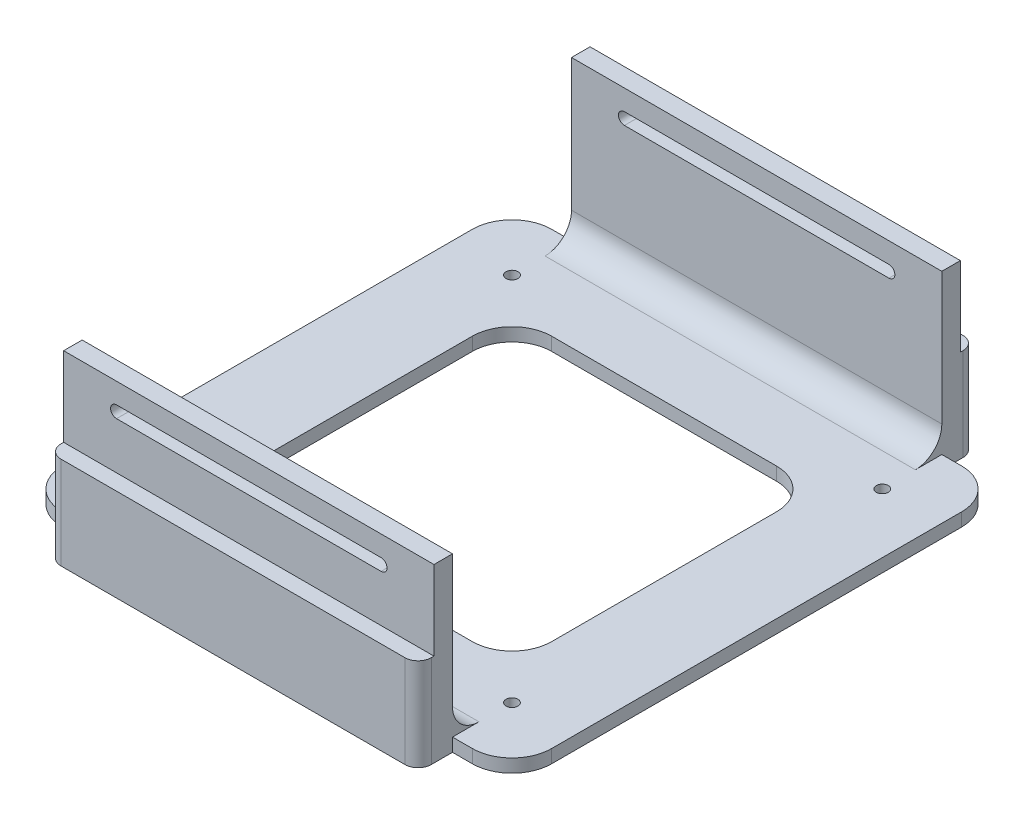
SolidWorks part; units mm, degrees
ref_plane "Front Plane" through (0, 0, 0) normal (0, 0, 1) x (1, 0, 0)
ref_plane "Top Plane" through (0, 0, 0) normal (0, 1, 0) x (1, 0, 0)
ref_plane "Right Plane" through (0, 0, 0) normal (1, 0, 0) x (0, 0, -1)
sketch "Sketch1" plane through (0, 0, 0) normal (0, 1, 0) x (1, 0, 0)
  line L0 (-60.9238, 116.5412) -> (-60.9238, 129.5412)
  line L1 (-83.4238, 116.5412) -> (101.5762, 116.5412)
  line L2 (-83.4238, 116.5412) -> (-83.4238, -68.4588)
  line L3 (-83.4238, -68.4588) -> (101.5762, -68.4588)
  line L4 (101.5762, 116.5412) -> (101.5762, -68.4588)
  line L5 (-60.9238, 129.5412) -> (79.0762, 129.5412)
  line L6 (79.0762, 129.5412) -> (79.0762, 116.5412)
  line L7 (-60.9238, -68.4588) -> (-60.9238, -81.4588)
  line L8 (-60.9238, -81.4588) -> (79.0762, -81.4588)
  line L9 (79.0762, -81.4588) -> (79.0762, -68.4588)
  dimension "D1" = 185
  dimension "D2" = 185
  dimension "D3" = 140
  dimension "D4" = 22.5
  dimension "D5" = 13
  dimension "D6" = 140
  dimension "D7" = 22.5
  dimension "D8" = 13
extrude "Boss-Extrude1" add sketch "Sketch1" along normal blind 5 contours L4 L1 L2 L3 | L8 L9 L3 L7 | L6 L5 L0 L1
sketch "Sketch2" plane through (0, 5, 0) normal (0, 1, 0) x (1, 0, 0)
  line L1 (-60.9238, 129.5412) -> (79.0762, 129.5412)
  line L2 (-60.9238, 129.5412) -> (-60.9238, 116.5412)
  line L3 (-60.9238, 116.5412) -> (79.0762, 116.5412)
  line L4 (79.0762, 129.5412) -> (79.0762, 116.5412)
  line L5 (-60.9238, -68.4588) -> (79.0762, -68.4588)
  line L6 (-60.9238, -68.4588) -> (-60.9238, -81.4588)
  line L7 (-60.9238, -81.4588) -> (79.0762, -81.4588)
  line L8 (79.0762, -68.4588) -> (79.0762, -81.4588)
extrude "Boss-Extrude2" add sketch "Sketch2" along normal blind 30
sketch "Sketch4" plane through (0, 35, 0) normal (0, 1, 0) x (1, 0, 0)
  line L0 (-60.9238, 129.5412) -> (-60.9238, 116.5412) construction
  line L1 (-60.9238, 123.5412) -> (79.0762, 123.5412)
  line L2 (-60.9238, 123.5412) -> (-60.9238, 116.5412)
  line L3 (-60.9238, 116.5412) -> (79.0762, 116.5412)
  line L4 (79.0762, 123.5412) -> (79.0762, 116.5412)
  line L5 (-60.9238, 116.5412) -> (79.0762, 116.5412) construction
  line L6 (79.0762, 116.5412) -> (79.0762, 129.5412) construction
  line L7 (79.0762, -81.4588) -> (79.0762, -68.4588) construction
  line L8 (-60.9238, -68.4588) -> (79.0762, -68.4588)
  line L9 (-60.9238, -68.4588) -> (-60.9238, -75.4588)
  line L10 (-60.9238, -75.4588) -> (79.0762, -75.4588)
  line L11 (79.0762, -68.4588) -> (79.0762, -75.4588)
  dimension "D1" = 7
  dimension "D2" = 7
extrude "Boss-Extrude3" add sketch "Sketch4" along normal blind 30
sketch "Sketch5" plane through (0, 0, 75.4588) normal (0, 0, 1) x (1, 0, 0)
  line L0 (-40.9238, 57.25) -> (59.0762, 57.25)
  line L1 (59.0762, 52.75) -> (-40.9238, 52.75)
  line L2 (-60.9238, 35) -> (79.0762, 35) construction
  line L3 (-60.9238, 65) -> (-60.9238, 35) construction
  arc A0 (59.0762, 57.25) -> (59.0762, 52.75) centre (59.0762, 55) cw
  arc A1 (-40.9238, 52.75) -> (-40.9238, 57.25) centre (-40.9238, 55) cw
  dimension "D1" = 2.25
  dimension "D2" = 20
  dimension "D3" = 100
  dimension "D4" = 20
extrude "Cut-Extrude1" cut sketch "Sketch5" against normal blind 1000
sketch "Sketch6" plane through (0, 5, 0) normal (0, 1, 0) x (1, 0, 0)
  line L1 (-48.4238, 81.5412) -> (66.5762, 81.5412)
  line L2 (-48.4238, 81.5412) -> (-48.4238, -33.4588)
  line L3 (-48.4238, -33.4588) -> (66.5762, -33.4588)
  line L4 (66.5762, 81.5412) -> (66.5762, -33.4588)
  line L5 (-60.9238, 116.5412) -> (79.0762, 116.5412) construction
  line L6 (101.5762, 116.5412) -> (101.5762, -68.4588) construction
  dimension "D1" = 115
  dimension "D2" = 115
  dimension "D3" = 35
  dimension "D4" = 35
extrude "Cut-Extrude2" cut sketch "Sketch6" against normal blind 1000
sketch "Sketch7" plane through (0, 5, 0) normal (0, 1, 0) x (1, 0, 0)
  line L0 (-83.4238, 116.5412) -> (-60.9238, 116.5412) construction
  line L2 (101.5762, 116.5412) -> (101.5762, -68.4588) construction
  circle A0 centre (-60.9238, 94.0412) radius 2.25
  circle A1 centre (79.0762, 94.0412) radius 2.25
  circle A2 centre (79.0762, -45.9588) radius 2.25
  circle A3 centre (-60.9238, -45.9588) radius 2.25
  point P10 (0, 0)
  dimension "D1" = 4.5
  dimension "D2" = 4.5
  dimension "D3" = 4.5
  dimension "D4" = 4.5
  dimension "D5" = 140
  dimension "D6" = 22.5
  dimension "D7" = 140
  dimension "D8" = 22.5
extrude "Cut-Extrude3" cut sketch "Sketch7" against normal blind 1000
fillet "Fillet1" radius 15 8 edges at (101.5762, 2.5, -116.5412) (101.5762, 2.5, 68.4588) (-83.4238, 2.5, -116.5412) (-83.4238, 2.5, 68.4588) (-48.4238, 2.5, 33.4588) (66.5762, 2.5, 33.4588) (66.5762, 2.5, -81.5412) (-48.4238, 2.5, -81.5412)
fillet "Fillet2" radius 5 4 edges at (79.0762, 17.5, -129.5412) (79.0762, 17.5, 81.4588) (-60.9238, 17.5, 81.4588) (-60.9238, 17.5, -129.5412)
fillet "Fillet3" radius 10 2 edges at (9.0762, 5, -116.5412) (9.0762, 5, 68.4588)
